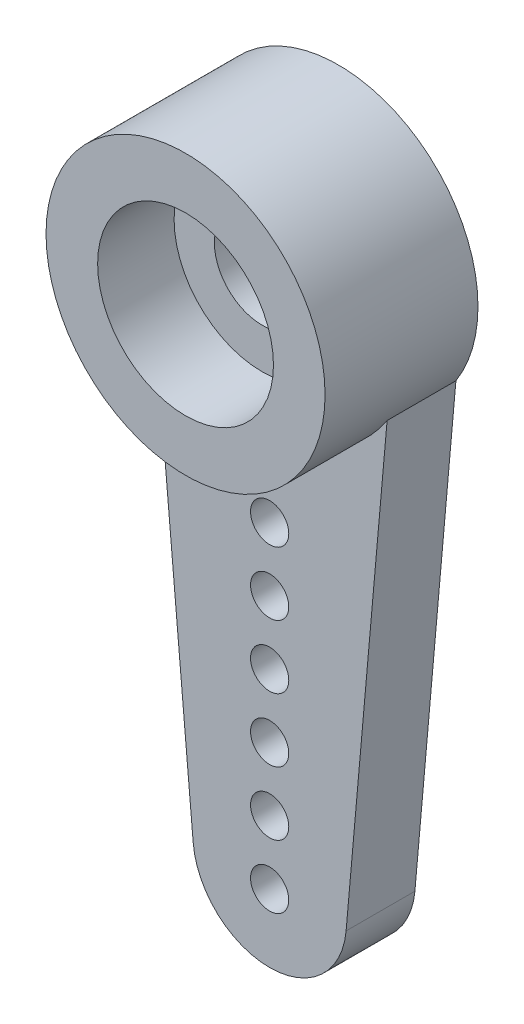
SolidWorks part; units mm, degrees
ref_plane "Plano frontal" through (0, 0, 0) normal (0, 0, 1) x (1, 0, 0)
ref_plane "Plano superior" through (0, 0, 0) normal (0, 1, 0) x (1, 0, 0)
ref_plane "Plano direito" through (0, 0, 0) normal (1, 0, 0) x (0, 0, -1)
sketch "Esboço1" plane through (0, 0, 0) normal (0, 0, 1) x (1, 0, 0)
  line L0 (0, 0) -> (0, 44.5352) construction
  line L1 (0, 0) -> (0, -40.9713) construction
  line L2 (3.0727, 20.2976) -> (2, 8.1976)
  line L3 (-3.0727, 20.2976) -> (-2, 8.1976)
  line L4 (0, 25.9176) -> (2.3044, 25.9176)
  circle A0 centre (0, 22.2676) radius 3.65
  circle A1 centre (0, 22.2676) radius 1.245
  arc A2 (-2, 8.1976) -> (2, 8.1976) centre (0, 8.3749) ccw
  dimension "D1" = 7.3
  dimension "D2" = 2.49
  dimension "D6" = 12.1
  dimension "D5" = 5.62
  dimension "D7" = 4
  dimension "D3" = 12.1
  dimension "D4" = 5.62
extrude "Ressalto-extrusão1" add sketch "Esboço1" along normal blind 1.8 contours L3 A2 L2 A0
sketch "Esboço2" plane through (0, 0, 0) normal (0, 0, -1) x (-1, 0, 0)
  line L0 (0, 22.2676) -> (0, 6.3671) construction
  line L1 (0, 22.2676) -> (0, 27.1379) construction
  arc A0 (-2, 8.1976) -> (2, 8.1976) centre (0, 8.3749) ccw construction
  circle A1 centre (0, 22.2676) radius 3.65
  circle A2 centre (0, 22.2676) radius 1.245
  dimension "D1" = 2.49
  dimension "D2" = 7.3
extrude "Ressalto-extrusão2" add sketch "Esboço2" against normal blind 4
sketch "Esboço3" plane through (0, 0, 4) normal (0, 0, 1) x (1, 0, 0)
  line L0 (0, 25.9176) -> (0, 18.6176) construction
  circle A0 centre (0, 22.2676) radius 3.65 construction
  circle A1 centre (0, 22.2676) radius 2.3
  circle A2 centre (0, 22.2676) radius 1.245
  dimension "D1" = 4.6
  dimension "D2" = 2.49
extrude "Corte-extrusão1" cut sketch "Esboço3" against normal blind 2
hole_wizard "Furo com folga de #00001" positions "Esboço6" profile "Esboço5" hole size "#0000" standard "Ansi Inch" end condition through all
sketch "Esboço6" plane through (0, 0, 1.8) normal (0, 0, 1) x (1, 0, 0)
  line L0 (0, 6.3671) -> (0, 18.6176) construction
  arc A0 (-2, 8.1976) -> (2, 8.1976) centre (0, 8.3749) ccw construction
  arc A1 (-3.0727, 20.2976) -> (3.0727, 20.2976) centre (0, 22.2676) ccw construction
  point P0 (0, 8.1471)
  dimension "D1" = 1.78
sketch "Esboço5" plane through (0, 8.1471, 1.8) normal (1, 0, 0) x (0, -1, 0)
  line L0 (0, 0) -> (0, 1.8)
  line L1 (0, 1.8) -> (0.45, 1.8)
  line L2 (0.45, 1.8) -> (0.45, 0)
  line L5 (0.45, 0) -> (0, 0)
  line L11 (0, -6.35) -> (0, 107.95) construction
  dimension "Thru Hole Dia." = 0.9
  dimension "Thru Hole Depth" = 1.8
hole_wizard "Furo com folga de #00002" positions "Esboço8" profile "Esboço7" hole size "#0000" standard "Ansi Inch" end condition through all
sketch "Esboço8" plane through (0, 0, 1.8) normal (0, 0, 1) x (1, 0, 0)
  circle A0 centre (0, 22.2676) radius 1.245 construction
  point P0 (0, 8.1471)
  point P10 (0, 9.8073)
  point P11 (0, 11.4676)
  point P12 (0, 13.1279)
  point P13 (0, 14.7881)
  point P14 (0, 16.4484)
  dimension "D2" = 10.8
  dimension "D1" = 6
sketch "Esboço7" plane through (0, 8.1471, 1.8) normal (1, 0, 0) x (0, -1, 0)
  line L0 (0, 0) -> (0, 1.8)
  line L1 (0, 1.8) -> (0.5, 1.8)
  line L2 (0.5, 1.8) -> (0.5, 0)
  line L5 (0.5, 0) -> (0, 0)
  line L11 (0, -6.35) -> (0, 107.95) construction
  dimension "Thru Hole Dia." = 1
  dimension "Thru Hole Depth" = 1.8
